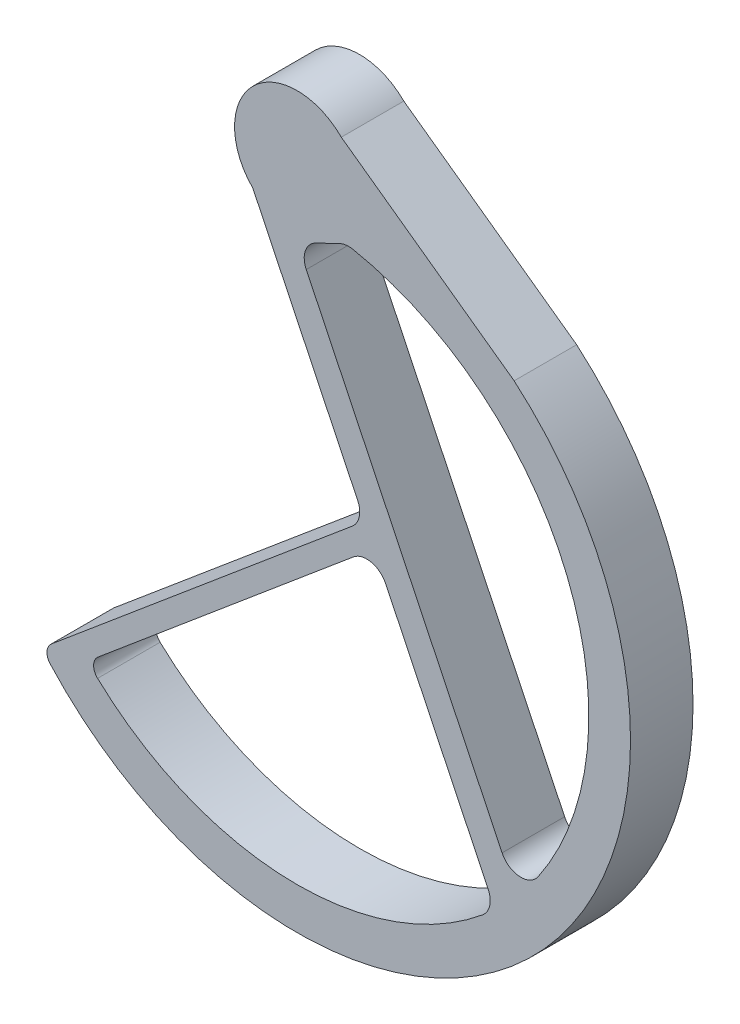
SolidWorks part; units mm, degrees
ref_plane "正面" through (0, 0, 0) normal (0, 0, 1) x (1, 0, 0)
ref_plane "平面" through (0, 0, 0) normal (0, 1, 0) x (1, 0, 0)
ref_plane "右側面" through (0, 0, 0) normal (1, 0, 0) x (0, 0, -1)
sketch "ｽｹｯﾁ4" plane through (0, 0, 0) normal (0, 0, 1) x (1, 0, 0)
  line L0 (0, 0.7897) -> (0, 0)
  line L1 (-53.6231, -124.9951) -> (-58.9406, -129.4571)
  line L3 (-10.6066, -10.6066) -> (14.5363, -62.8896)
  line L4 (-53.6231, -124.9951) -> (13.2442, -68.8868)
  line L5 (21.2324, -76.8138) -> (45.8448, -127.9938)
  line L6 (10.6066, 10.6066) -> (52.0762, -19.2705)
  line L7 (-58.0696, -135.2532) -> (-57.9498, -135.1527)
  line L8 (-47.7477, -126.5866) -> (13.5112, -75.1515)
  arc A1 (-59.2335, -133.7716) -> (52.0762, -19.2705) centre (0, -80) ccw
  arc A2 (-47.8702, -131.073) -> (44.5187, -134.0193) centre (0, -80) ccw
  arc A3 (10.6066, 10.6066) -> (-10.6066, -10.6066) centre (0, 0) ccw
  arc A4 (-59.2335, -133.7716) -> (-58.9406, -129.4571) centre (-57.0123, -131.7552) cw
  arc A5 (-47.8702, -131.073) -> (-47.7477, -126.5866) centre (-45.8186, -128.8841) cw
  arc A6 (13.5112, -75.1515) -> (21.2324, -76.8138) centre (16.7264, -78.9807) cw
  arc A7 (13.2442, -68.8868) -> (14.5363, -62.8896) centre (10.0302, -65.0566) ccw
  arc A8 (45.8448, -127.9938) -> (44.5187, -134.0193) centre (41.3388, -130.1608) cw
  point P18 (-61.2836, -131.423)
  point P21 (-50.2744, -128.7081)
  point P24 (18.4421, -71.0114)
  dimension "D3" = 140
  dimension "D4" = 30
  dimension "D5" = 5
  dimension "D6" = 3
  dimension "D7" = 3
  dimension "D8" = 5
  dimension "D9" = 5
  dimension "D10" = 5
  dimension "D2" = 5
extrude "ﾎﾞｽ - 押し出し1" add sketch "ｽｹｯﾁ4" along normal blind 15
sketch "ｽｹｯﾁ6" plane through (0, 0, 15) normal (0, 0, 1) x (1, 0, 0)
  line L6 (49.1896, -118.7973) -> (2.2018, -21.089)
  line L7 (6.4834, -13.4819) -> (4.5408, -14.416)
  line L8 (6.4834, -13.4819) -> (10.2197, -11.6851)
  arc A0 (57.8261, -119.448) -> (13.3394, -11.2828) centre (0, -80) ccw
  arc A1 (2.2018, -21.089) -> (4.5408, -14.416) centre (6.7078, -18.9221) cw
  arc A2 (13.3394, -11.2828) -> (10.2197, -11.6851) centre (12.3866, -16.1911) ccw
  arc A3 (57.8261, -119.448) -> (49.1896, -118.7973) centre (53.6956, -116.6303) cw
  point P7 (0.0348, -16.583)
  point P14 (52.6925, -126.0814)
  dimension "D3" = 121.502
  dimension "D4" = 70
  dimension "D1" = 5
  dimension "D2" = 5
  dimension "D5" = 5
  dimension "D6" = 90
extrude "ｶｯﾄ - 押し出し1" cut sketch "ｽｹｯﾁ6" against normal blind 15
sketch "ｽｹｯﾁ8" plane through (0, 0, 0) normal (0, 0, -1) x (-1, 0, 0)
  circle A0 centre (0, 0) radius 10
extrude "ｶｯﾄ - 押し出し3" cut sketch "ｽｹｯﾁ8" against normal blind 2
